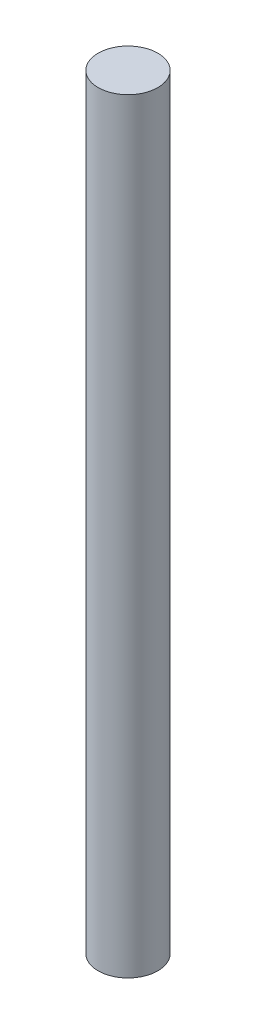
SolidWorks part; units mm, degrees
ref_plane "Front Plane" through (0, 0, 0) normal (0, 0, 1) x (1, 0, 0)
ref_plane "Top Plane" through (0, 0, 0) normal (0, 1, 0) x (1, 0, 0)
ref_plane "Right Plane" through (0, 0, 0) normal (1, 0, 0) x (0, 0, -1)
sketch "Sketch1" plane through (0, 0, 0) normal (0, 1, 0) x (1, 0, 0)
  circle A0 centre (1750.0001, -1750.0001) radius 1950
  dimension "D1" = 3900
extrude "Boss-Extrude1" add sketch "Sketch1" against normal blind 50000 separate body
scale "Scale1" scale about centroid uniform scaling yes scale factor 0.001
